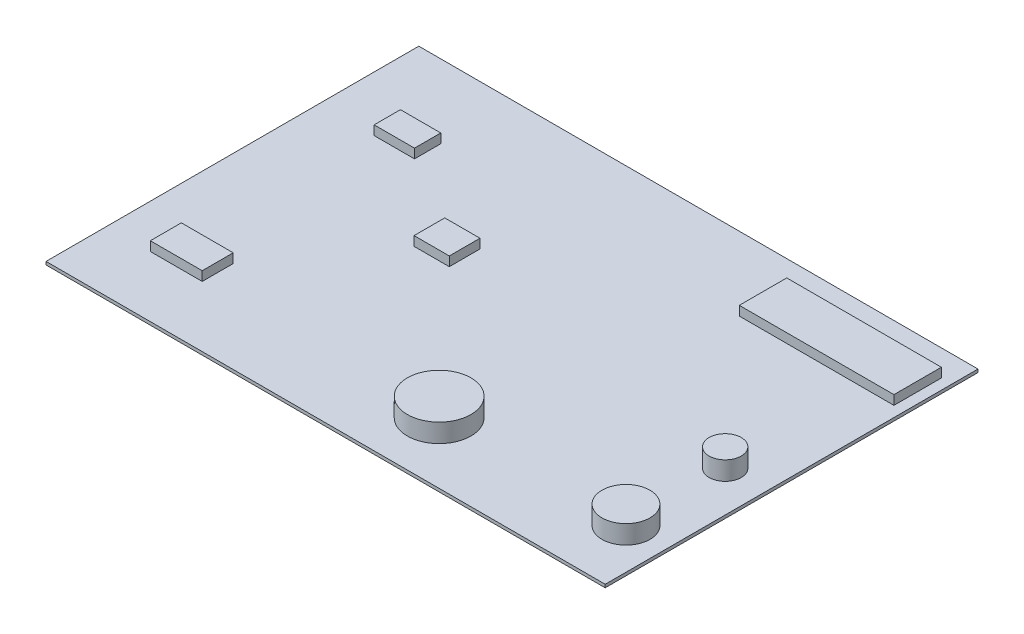
SolidWorks part; units mm, degrees
ref_plane "前视基准面" through (0, 0, 0) normal (0, 0, 1) x (1, 0, 0)
ref_plane "上视基准面" through (0, 0, 0) normal (0, 1, 0) x (1, 0, 0)
ref_plane "右视基准面" through (0, 0, 0) normal (1, 0, 0) x (0, 0, -1)
sketch "草图1" plane through (0, 0, 0) normal (0, 1, 0) x (1, 0, 0)
  line L1 (-90, -60) -> (90, -60)
  line L2 (-90, -60) -> (-90, 60)
  line L3 (-90, 60) -> (90, 60)
  line L4 (90, -60) -> (90, 60)
  line L5 (-90, -60) -> (90, 60) construction
  line L6 (-90, 60) -> (90, -60) construction
  point P0 (0, 0)
  dimension "D1" = 180
  dimension "D2" = 120
extrude "凸台-拉伸1" add sketch "草图1" along normal blind 1
sketch "草图2" plane through (0, 1, 0) normal (0, 1, 0) x (1, 0, 0)
  line L1 (-72.2537, 36.3383) -> (-59.2684, 36.3383)
  line L2 (-72.2537, 36.3383) -> (-72.2537, 27.8803)
  line L3 (-72.2537, 27.8803) -> (-59.2684, 27.8803)
  line L4 (-59.2684, 36.3383) -> (-59.2684, 27.8803)
  line L5 (-75.9696, -30.4686) -> (-59.2684, -30.4686)
  line L6 (-75.9696, -30.4686) -> (-75.9696, -40.4487)
  line L7 (-75.9696, -40.4487) -> (-59.2684, -40.4487)
  line L8 (-59.2684, -30.4686) -> (-59.2684, -40.4487)
  line L9 (-34.9517, 13.304) -> (-23.6168, 13.304)
  line L10 (-34.9517, 13.304) -> (-34.9517, 3.4304)
  line L11 (-34.9517, 3.4304) -> (-23.6168, 3.4304)
  line L12 (-23.6168, 13.304) -> (-23.6168, 3.4304)
  line L13 (36.8266, 51.608) -> (86.6037, 51.608)
  line L14 (36.8266, 51.608) -> (36.8266, 36.3383)
  line L15 (36.8266, 36.3383) -> (86.6037, 36.3383)
  line L16 (86.6037, 51.608) -> (86.6037, 36.3383)
extrude "凸台-拉伸2" add sketch "草图2" along normal blind 3
sketch "草图3" plane through (0, 1, 0) normal (0, 1, 0) x (1, 0, 0)
  circle A0 centre (76.9816, -8.3586) radius 5.1643
  circle A1 centre (76.9816, -40.2957) radius 7.7249
  circle A2 centre (16.8475, -40.2957) radius 10.2339
  point P6 (76.9816, -8.3586)
extrude "凸台-拉伸3" add sketch "草图3" along normal blind 6
